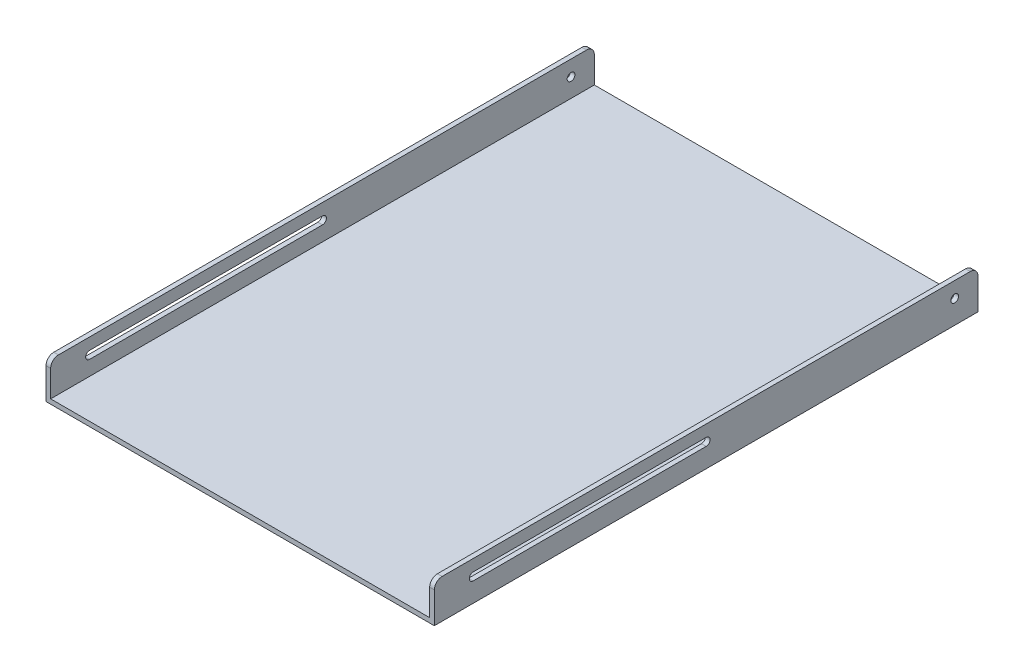
SolidWorks part; units mm, degrees
ref_plane "Front Plane" through (0, 0, 0) normal (0, 0, 1) x (1, 0, 0)
ref_plane "Top Plane" through (0, 0, 0) normal (0, 1, 0) x (1, 0, 0)
ref_plane "Right Plane" through (0, 0, 0) normal (1, 0, 0) x (0, 0, -1)
sketch "Sketch1" plane through (0, 0, 0) normal (0, 0, 1) x (1, 0, 0)
  line L0 (-250, 0) -> (250, 0)
  line L1 (250, 0) -> (250, 50)
  line L2 (-250, 0) -> (-250, 50)
  dimension "D1" = 500
  dimension "D2" = 250
  dimension "D3" = 50
extrude "Extrude-Thin1" add sketch "Sketch1" along normal mid plane 700 thin thin type one direction wall 6
sketch "Sketch2" plane through (250, 0, 0) normal (1, 0, 0) x (0, 0, -1)
  line L0 (-300, 30) -> (0, 30) construction
  line L1 (-300, 35) -> (0, 35)
  line L2 (-300, 25) -> (0, 25)
  line L3 (350, 50) -> (350, 0) construction
  line L4 (-350, 0) -> (350, 0) construction
  circle A0 centre (320, 30) radius 5
  arc A1 (-300, 35) -> (-300, 25) centre (-300, 30) ccw
  arc A2 (0, 25) -> (0, 35) centre (0, 30) ccw
  point P4 (-150, 30)
  point P11 (0, 0)
  point P12 (0, 0)
  point P13 (276.0773, 28.4252)
  dimension "D1" = 10
  dimension "D2" = 30
  dimension "D3" = 30
  dimension "D4" = 150
  dimension "D5" = 300
  dimension "D6" = 10
extrude "Cut-Extrude1" cut sketch "Sketch2" against normal through all both and the other way through all
fillet "Fillet1" radius 10 4 edges at (247, 50, 350) (-247, 50, 350) (247, 50, -350) (-247, 50, -350)
